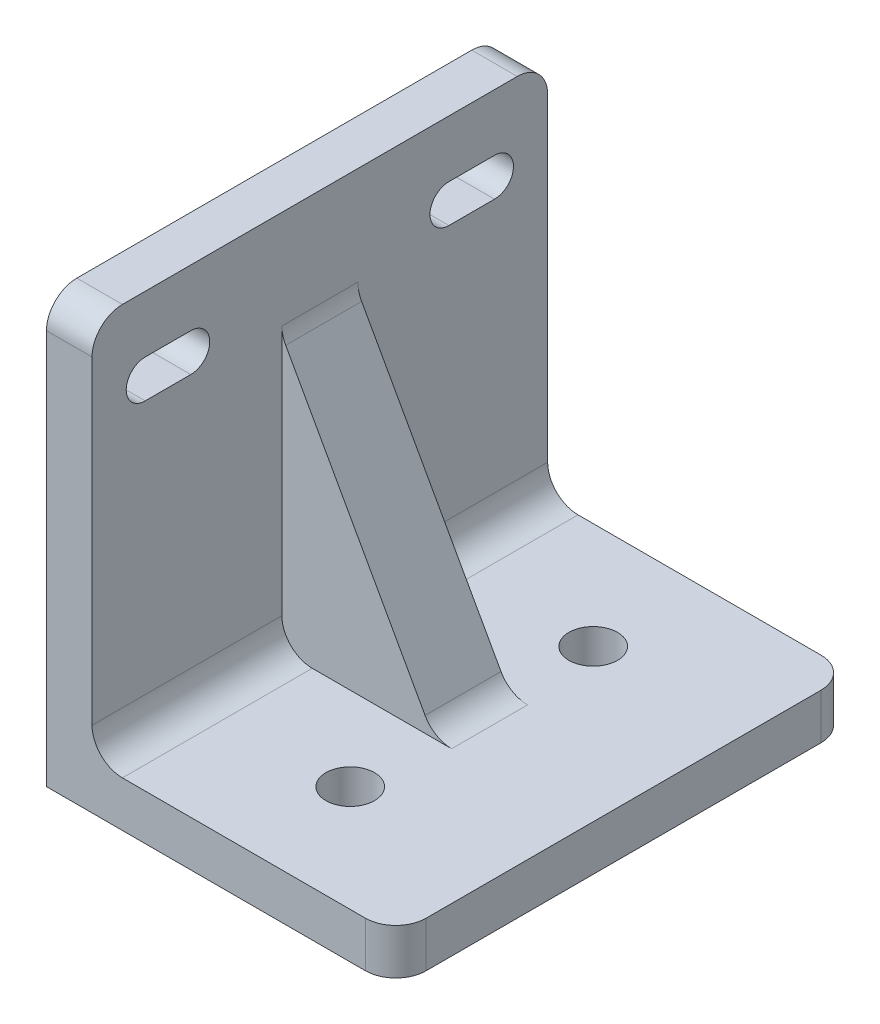
SolidWorks part; units mm, degrees
ref_plane "前视基准面" through (0, 0, 0) normal (0, 0, 1) x (1, 0, 0)
ref_plane "上视基准面" through (0, 0, 0) normal (0, 1, 0) x (1, 0, 0)
ref_plane "右视基准面" through (0, 0, 0) normal (1, 0, 0) x (0, 0, -1)
other "Configuration Table"
sketch "草图1" plane through (0, 0, 0) normal (0, 0, 1) x (1, 0, 0)
  line L0 (0, 0) -> (0, 25)
  line L1 (0, 25) -> (-3, 25)
  line L2 (-3, 25) -> (-3, -3)
  line L3 (-3, -3) -> (20, -3)
  line L4 (20, -3) -> (20, 0)
  line L5 (20, 0) -> (0, 0)
  dimension "D1" = 3
  dimension "D2" = 20
  dimension "D3" = 25
extrude "凸台-拉伸1" add sketch "草图1" along normal mid plane 30
sketch "草图2" plane through (0, 0, 0) normal (0, 1, 0) x (1, 0, 0)
  line L0 (0, 0) -> (20, 0) construction
  line L1 (20, -15) -> (20, 15) construction
  line L2 (0, -15) -> (0, 15) construction
  circle A0 centre (10, -8) radius 1.6
  circle A1 centre (10, 8) radius 1.6
  dimension "D1" = 3.2
  dimension "D2" = 16
  dimension "D3" = 10
extrude "切除-拉伸1" cut sketch "草图2" against normal blind 25
sketch "草图3" plane through (-3, 0, 0) normal (-1, 0, 0) x (0, 0, 1)
  line L0 (0, 0) -> (0, 25) construction
  line L1 (15, 25) -> (-15, 25) construction
  line L2 (-11.5, 20) -> (-8.5, 20) construction
  line L3 (-11.5, 21.25) -> (-8.5, 21.25)
  line L4 (-11.5, 18.75) -> (-8.5, 18.75)
  line L5 (11.5, 20) -> (8.5, 20) construction
  line L6 (11.5, 21.25) -> (8.5, 21.25)
  line L7 (11.5, 18.75) -> (8.5, 18.75)
  circle A0 centre (-11.5, 20) radius 1.25 construction
  circle A1 centre (11.5, 20) radius 1.25 construction
  arc A2 (-11.5, 21.25) -> (-11.5, 18.75) centre (-11.5, 20) ccw
  arc A3 (-8.5, 18.75) -> (-8.5, 21.25) centre (-8.5, 20) ccw
  arc A4 (11.5, 21.25) -> (11.5, 18.75) centre (11.5, 20) cw
  arc A5 (8.5, 18.75) -> (8.5, 21.25) centre (8.5, 20) cw
  point P9 (-10, 20)
  point P16 (10, 20)
  dimension "D1" = 2.5
  dimension "D2" = 23
  dimension "D3" = 5
  dimension "D4" = 3
extrude "切除-拉伸2" cut sketch "草图3" against normal blind 25
sketch "草图4" plane through (0, 0, 0) normal (0, 0, 1) x (1, 0, 0)
  line L0 (0, 18) -> (10, 0)
  line L2 (20, 0) -> (0, 0) construction
  line L3 (0, 0) -> (0, 25) construction
  dimension "D1" = 18
rib "筋1" sketch "草图4" sketch "草图4" thickness 5 extrusion direction parallel to sketch draft on no parameters "D1"=5
fillet "圆角1" radius 2 8 edges at (20, -1.5, 15) (20, -1.5, -15) (-1.5, 25, -15) (-1.5, 25, 15) (0, 18, 0) (0, 0, -8.75) (10, 0, 0) (0, 0, 8.75)
